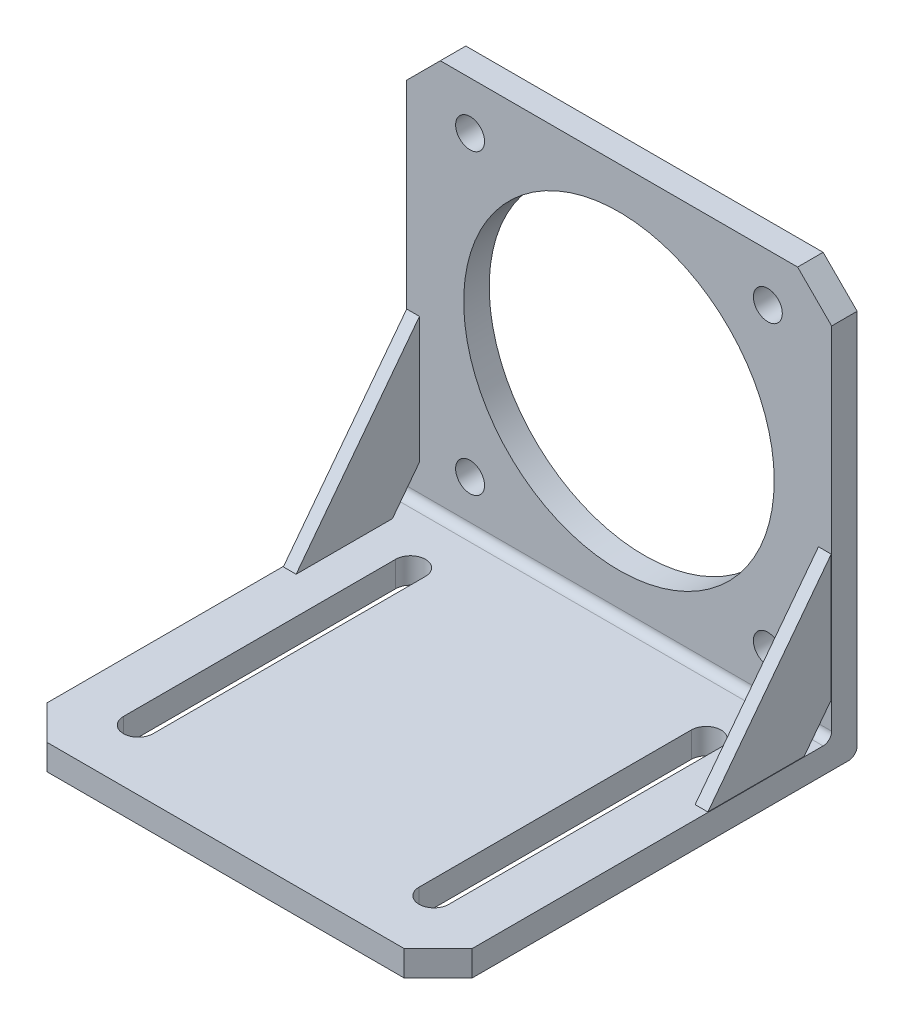
SolidWorks part; units mm, degrees
ref_plane "Front Plane" through (0, 0, 0) normal (0, 0, 1) x (1, 0, 0)
ref_plane "Top Plane" through (0, 0, 0) normal (0, 1, 0) x (1, 0, 0)
ref_plane "Right Plane" through (0, 0, 0) normal (1, 0, 0) x (0, 0, -1)
sketch "Sketch1" plane through (0, 0, 0) normal (0, 0, 1) x (1, 0, 0)
  line L1 (-50, -6.042) -> (50, -6.042)
  line L2 (-50, -6.042) -> (-50, 92.458)
  line L3 (-50, 92.458) -> (50, 92.458)
  line L4 (50, -6.042) -> (50, 92.458)
  line L6 (0, 92.458) -> (0, -0.042) construction
  line L8 (-35, 81.208) -> (35, 81.208) construction
  line L9 (-35, 81.208) -> (-35, 11.208) construction
  line L10 (-35, 11.208) -> (35, 11.208) construction
  line L11 (35, 81.208) -> (35, 11.208) construction
  line L12 (-35, 81.208) -> (35, 11.208) construction
  line L13 (-35, 11.208) -> (35, 81.208) construction
  circle A0 centre (0, 46.208) radius 36.5
  circle A1 centre (-35, 81.208) radius 3.4
  circle A2 centre (35, 81.208) radius 3.4
  circle A3 centre (35, 11.208) radius 3.4
  circle A4 centre (-35, 11.208) radius 3.4
  point P27 (0, 49.25)
  point P28 (0, 46.208)
  dimension "D4" = 73
  dimension "D5" = 6.8
  dimension "D1" = 100
  dimension "D2" = 70
  dimension "D8" = 4
extrude "Boss-Extrude1" add sketch "Sketch1" along normal blind 6
sketch "Sketch2" plane through (0, 0, 6) normal (0, 0, 1) x (1, 0, 0)
  line L0 (50, -6.042) -> (50, 92.458) construction
  line L1 (-50, -6.042) -> (50, -6.042)
  line L2 (-50, -6.042) -> (-50, -0.042)
  line L3 (-50, -0.042) -> (50, -0.042)
  line L4 (50, -6.042) -> (50, -0.042)
  dimension "D1" = 6
extrude "Boss-Extrude2" add sketch "Sketch2" along normal blind 92.5
chamfer "Chamfer1" distance 8 angle 45 4 edges at (50, -3.042, 98.5) (-50, -3.042, 98.5) (50, 92.458, 3) (-50, 92.458, 3)
sketch "Sketch3" plane through (0, -0.042, 0) normal (0, 1, 0) x (1, 0, 0)
  line L0 (-34.75, -6) -> (-34.75, -98.5) construction
  line L1 (50, -6) -> (-50, -6) construction
  line L2 (42, -98.5) -> (-42, -98.5) construction
  line L3 (-34.75, -84.25) -> (-34.75, -20.25) construction
  line L4 (-38.25, -84.25) -> (-38.25, -20.25)
  line L5 (-31.25, -84.25) -> (-31.25, -20.25)
  line L6 (0, -6) -> (0, -98.5) construction
  line L7 (34.75, -84.25) -> (34.75, -20.25) construction
  line L8 (38.25, -84.25) -> (38.25, -20.25)
  line L9 (31.25, -84.25) -> (31.25, -20.25)
  arc A0 (-38.25, -84.25) -> (-31.25, -84.25) centre (-34.75, -84.25) ccw
  arc A1 (-31.25, -20.25) -> (-38.25, -20.25) centre (-34.75, -20.25) ccw
  arc A2 (38.25, -84.25) -> (31.25, -84.25) centre (34.75, -84.25) cw
  arc A3 (31.25, -20.25) -> (38.25, -20.25) centre (34.75, -20.25) cw
  point P8 (-34.75, -52.25)
  point P17 (34.75, -52.25)
  dimension "D1" = 7
  dimension "D2" = 64
  dimension "D3" = 69.5
extrude "Cut-Extrude1" cut sketch "Sketch3" against normal through all
sketch "Sketch4" plane through (-50, 0, 0) normal (-1, 0, 0) x (0, 0, 1)
  line L0 (6, 37.958) -> (35, -0.042)
  line L1 (6, 84.458) -> (6, -0.042) construction
  line L2 (90.5, -0.042) -> (6, -0.042) construction
  line L3 (35, -0.042) -> (12.3571, -0.042)
  line L4 (6, 8.2879) -> (6, 37.958)
  line L5 (6, 8.2879) -> (12.3571, -0.042)
  dimension "D3" = 18
extrude "Boss-Extrude3" add sketch "Sketch4" against normal blind 3 from offset 0.1 offset against normal yes
sketch "Sketch5" plane through (50, 0, 0) normal (1, 0, 0) x (0, 0, -1)
  line L3 (-6, 8.2879) -> (-6, 37.958)
  line L4 (-6, 37.958) -> (-35, -0.042)
  line L5 (-35, -0.042) -> (-12.3571, -0.042)
  line L6 (-6, 8.2879) -> (-6, 37.958)
  line L7 (-6, 37.958) -> (-35, -0.042)
  line L8 (-35, -0.042) -> (-12.3571, -0.042)
  line L10 (-12.3571, -0.042) -> (-6, 8.2879)
  line L11 (-12.3571, -0.042) -> (-6, 8.2879)
  dimension "D1" = 0
extrude "Boss-Extrude4" add sketch "Sketch5" against normal blind 3 from offset 0.1 offset against normal yes
fillet "Fillet1" radius 2 2 edges at (0, -6.042, 0) (0, -0.042, 6)
